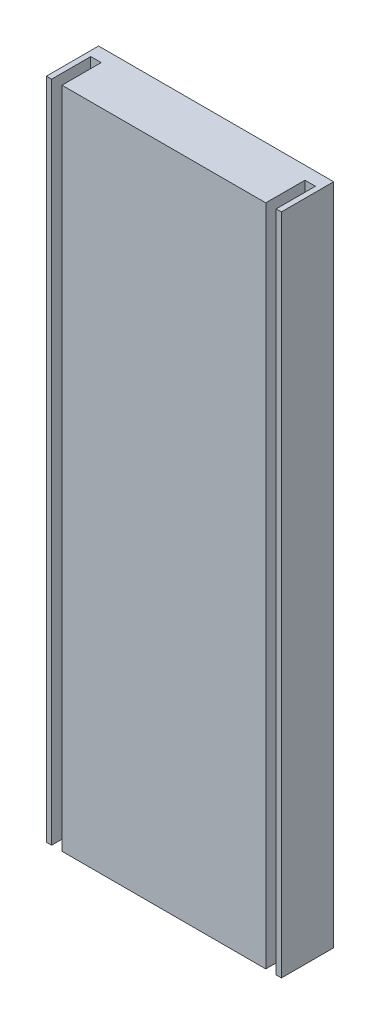
SolidWorks part; units mm, degrees
ref_plane "Спереди" through (0, 0, 0) normal (0, 0, 1) x (1, 0, 0)
ref_plane "Сверху" through (0, 0, 0) normal (0, 1, 0) x (1, 0, 0)
ref_plane "Справа" through (0, 0, 0) normal (1, 0, 0) x (0, 0, -1)
sketch "Эскиз1" plane through (0, 0, 0) normal (0, 1, 0) x (1, 0, 0)
  line L0 (-31.6163, -7.2411) -> (-31.6163, 7.7589)
  line L1 (-33.6163, 12.7589) -> (56.3837, 12.7589)
  line L2 (-33.6163, 12.7589) -> (-33.6163, -7.2411)
  line L3 (-33.6163, -7.2411) -> (-31.6163, -7.2411)
  line L4 (56.3837, 12.7589) -> (56.3837, -7.2411)
  line L5 (-31.6163, 7.7589) -> (-27.6163, 7.7589)
  line L6 (-27.6163, 7.7589) -> (-27.6163, -7.2411)
  line L7 (54.3837, -7.2411) -> (54.3837, 7.7589)
  line L8 (54.3837, 7.7589) -> (50.3837, 7.7589)
  line L9 (50.3837, 7.7589) -> (50.3837, -7.2411)
  line L10 (-27.6163, -7.2411) -> (50.3837, -7.2411)
  line L11 (54.3837, -7.2411) -> (56.3837, -7.2411)
  dimension "D1" = 90
  dimension "D2" = 20
  dimension "D3" = 4
  dimension "D4" = 4
  dimension "D5" = 2
  dimension "D6" = 2
  dimension "D7" = 15
  dimension "D8" = 15
extrude "Бобышка-Вытянуть1" add sketch "Эскиз1" along normal blind 254
